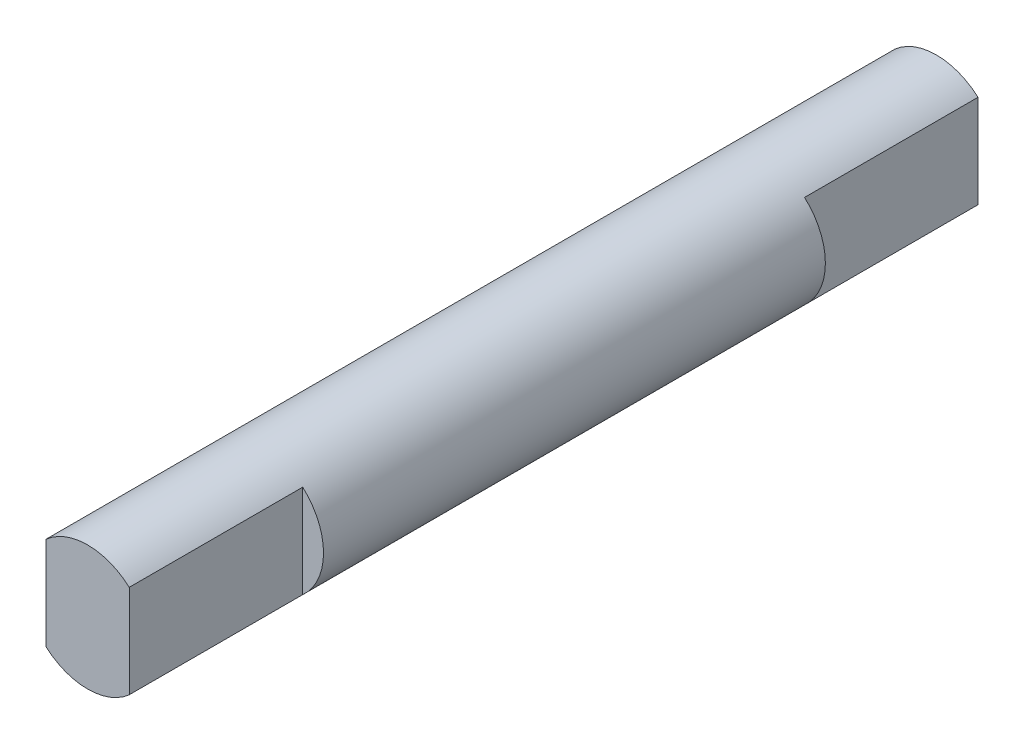
SolidWorks part; units mm, degrees
ref_plane "Alzado" through (0, 0, 0) normal (0, 0, 1) x (1, 0, 0)
ref_plane "Planta" through (0, 0, 0) normal (0, 1, 0) x (1, 0, 0)
ref_plane "Vista lateral" through (0, 0, 0) normal (1, 0, 0) x (0, 0, -1)
sketch "Croquis1" plane through (0, 0, 0) normal (0, 0, 1) x (1, 0, 0)
  circle A0 centre (0, 0) radius 2.7
  dimension "D1" = 5.4
extrude "Saliente-Extruir1" add sketch "Croquis1" along normal blind 36.7
sketch "Croquis2" plane through (0, 0, 0) normal (0, 0, -1) x (-1, 0, 0)
  line L0 (0, 0.9465) -> (0, 0) construction
  line L1 (0, 0) -> (-1.8, 0) construction
  line L2 (-1.8, -2.0125) -> (-1.8, 2.0125)
  line L3 (1.8, -2.0125) -> (1.8, 2.0125)
  arc A0 (-1.8, -2.0125) -> (1.8, -2.0125) centre (0, 0) ccw
  arc A1 (1.8, 2.0125) -> (-1.8, 2.0125) centre (0, 0) ccw
  point P8 (-1.8, 0)
  circle M7 centre (0, 0) radius 2.7
  dimension "D2" = 2.7
  dimension "D1" = 1.8
extrude "Cortar-Extruir1" cut sketch "Croquis2" against normal blind 7.5 contours L2 M7 | L3 M7
sketch "Croquis3" plane through (0, 0, 36.7) normal (0, 0, 1) x (1, 0, 0)
  line L0 (0, 0.597) -> (0, 0) construction
  line L1 (0, 0) -> (-1.8, 0) construction
  line L2 (-1.8, -2.0125) -> (-1.8, 2.0125)
  line L3 (1.8, -2.0125) -> (1.8, 2.0125)
  arc A0 (-1.8, -2.0125) -> (1.8, -2.0125) centre (0, 0) ccw
  arc A1 (1.8, 2.0125) -> (-1.8, 2.0125) centre (0, 0) ccw
  point P10 (-1.8, 0)
  circle M7 centre (0, 0) radius 2.7
  dimension "D2" = 2.7
  dimension "D1" = 1.8
extrude "Cortar-Extruir2" cut sketch "Croquis3" against normal blind 7.5 contours L3 M7 | L2 M7
